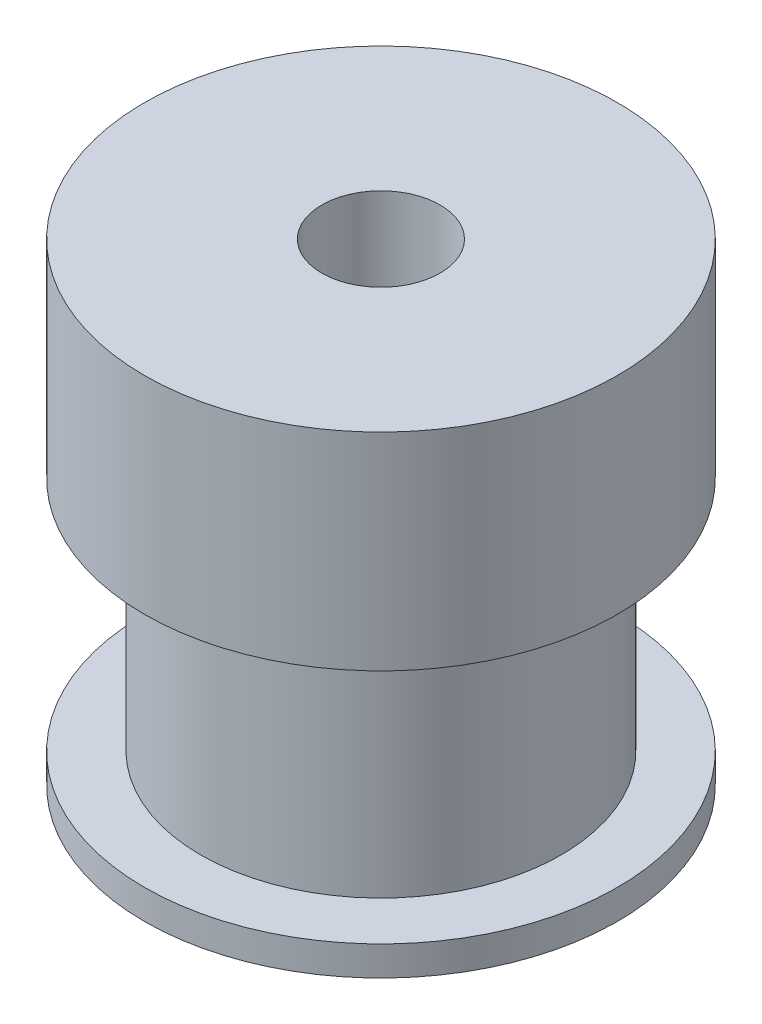
SolidWorks part; units mm, degrees
ref_plane "Plan de face" through (0, 0, 0) normal (0, 0, 1) x (1, 0, 0)
ref_plane "Plan de dessus" through (0, 0, 0) normal (0, 1, 0) x (1, 0, 0)
ref_plane "Plan de droite" through (0, 0, 0) normal (1, 0, 0) x (0, 0, -1)
sketch "Esquisse1" plane through (0, 0, 0) normal (0, 1, 0) x (1, 0, 0)
  circle A0 centre (0, 0) radius 8
extrude "Extrusion1" add sketch "Esquisse1" along normal blind 1
sketch "Esquisse2" plane through (0, 1, 0) normal (0, 1, 0) x (-1, 0, 0)
  circle A0 centre (0, 0) radius 6.1
extrude "Extrusion2" add sketch "Esquisse2" along normal blind 8
sketch "Esquisse3" plane through (0, 9, 0) normal (0, 1, 0) x (-1, 0, 0)
  circle A0 centre (0, 0) radius 8
extrude "Extrusion3" add sketch "Esquisse3" along normal blind 7
sketch "Esquisse4" plane through (0, 16, 0) normal (0, 1, 0) x (-1, 0, 0)
  circle A0 centre (0, 0) radius 2
extrude "Extrusion4" cut sketch "Esquisse4" against normal through all
